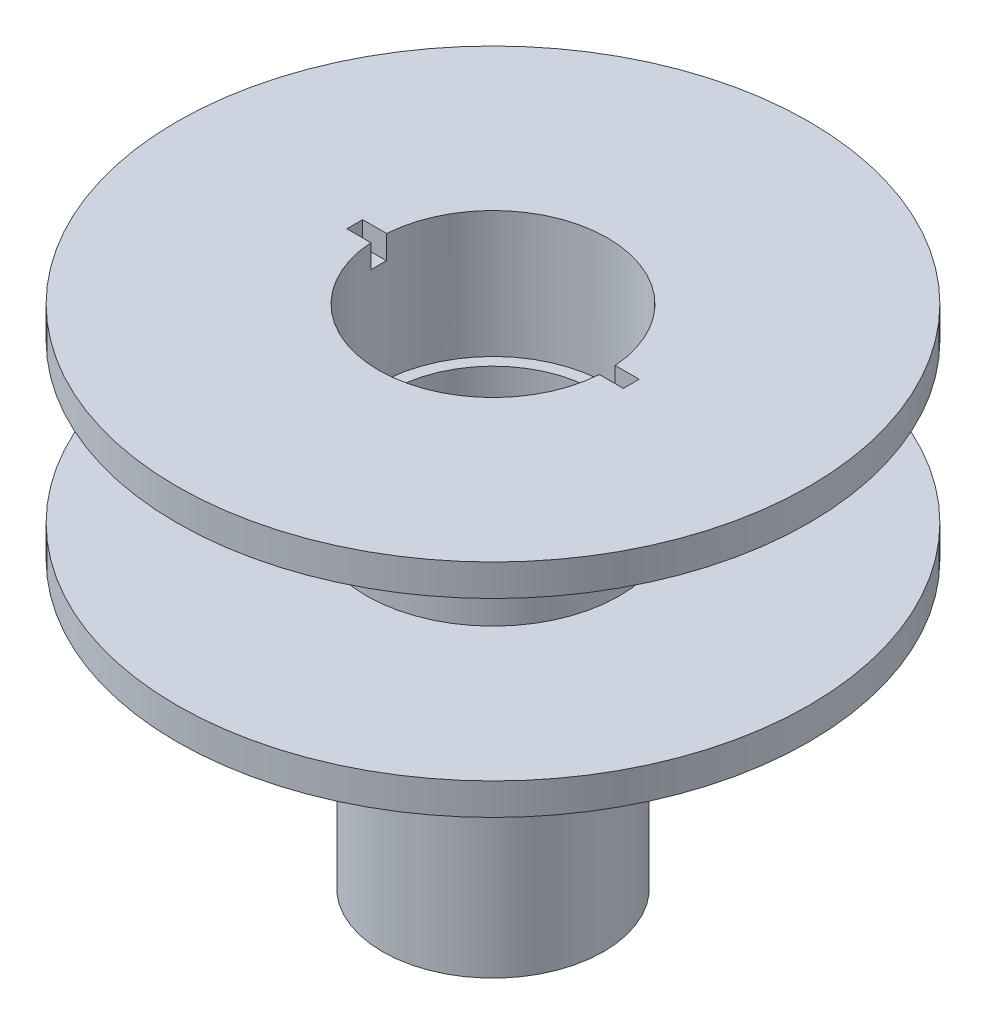
SolidWorks part; units mm, degrees
ref_plane "Front Plane" through (0, 0, 0) normal (0, 0, 1) x (1, 0, 0)
ref_plane "Top Plane" through (0, 0, 0) normal (0, 1, 0) x (1, 0, 0)
ref_plane "Right Plane" through (0, 0, 0) normal (1, 0, 0) x (0, 0, -1)
sketch "Sketch1" plane through (0, 0, 0) normal (1, 0, 0) x (0, 0, -1)
  line L0 (0, 28.0586) -> (0, -24.3494) construction
  line L5 (-16, 3.3739) -> (-40, 3.3739)
  line L6 (-40, 3.3739) -> (-40, -0.6261)
  line L7 (-40, -0.6261) -> (-14.5, -0.6261)
  line L8 (-13, -0.6261) -> (-13, 11.3739)
  line L14 (-16, 3.3739) -> (-16, 23.3739)
  line L15 (-16, 23.3739) -> (-14.5, 23.3739)
  line L16 (-14.5, 23.3739) -> (-14.5, 11.3739)
  line L17 (-13, 11.3739) -> (-14.5, 11.3739)
  line L19 (-14, -36.6261) -> (-13, -36.6261)
  line L20 (-13, -36.6261) -> (-13, -0.6261)
  line L21 (-14, -0.6261) -> (-14, -36.6261)
  line L22 (-14.5, -0.6261) -> (-14, -0.6261)
  dimension "D1" = 29
  dimension "D3" = 12
  dimension "D4" = 1.5
  dimension "D5" = 4
  dimension "D6" = 28
  dimension "D7" = 80
  dimension "D9" = 36
revolve "Revolve1" add sketch "Sketch1" angle 360 about L0
ref_plane "Plane1" through (0, 13.3739, 0) normal (0, 1, 0) x (1, 0, 0)
mirror "Mirror3" about plane through (0, 13.3739, 0) normal (0, 1, 0) of "Revolve1"
sketch "Sketch2" plane through (0, 11.3739, 0) normal (0, 1, 0) x (1, 0, 0)
  circle A0 centre (0, 0) radius 14.5
extrude "Cut-Extrude1" cut sketch "Sketch2" along normal blind 66
sketch "Sketch3" plane through (0, 27.3739, 0) normal (0, 1, 0) x (1, 0, 0)
  line L1 (17.5, -1) -> (-17.5, -1)
  line L2 (17.5, -1) -> (17.5, 1)
  line L3 (17.5, 1) -> (-17.5, 1)
  line L4 (-17.5, -1) -> (-17.5, 1)
  line L5 (17.5, -1) -> (-17.5, 1) construction
  line L6 (17.5, 1) -> (-17.5, -1) construction
  point P0 (0, 0)
  dimension "D1" = 2
  dimension "D2" = 35
extrude "Cut-Extrude2" cut sketch "Sketch3" against normal blind 3
